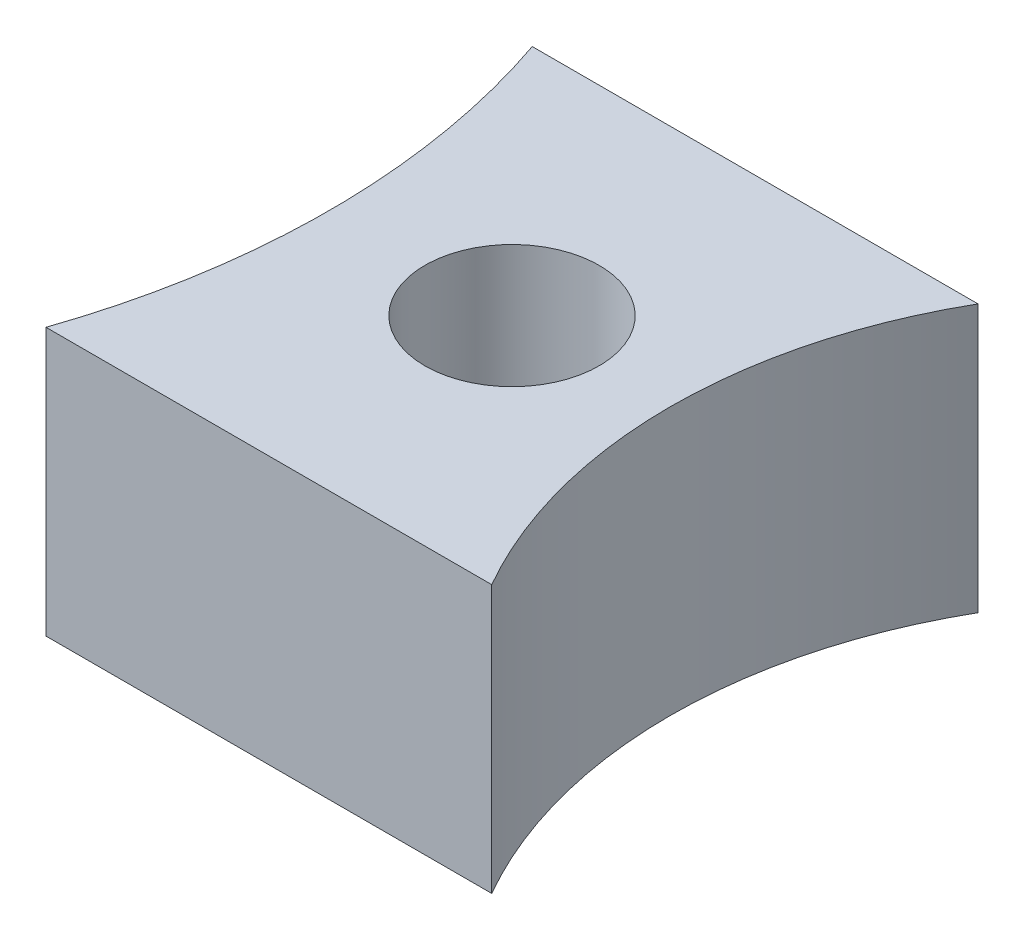
SolidWorks part; units mm, degrees
ref_plane "Front Plane" through (0, 0, 0) normal (0, 0, 1) x (1, 0, 0)
ref_plane "Top Plane" through (0, 0, 0) normal (0, 1, 0) x (1, 0, 0)
ref_plane "Right Plane" through (0, 0, 0) normal (1, 0, 0) x (0, 0, -1)
sketch "Sketch1" plane through (0, 0, 0) normal (0, 1, 0) x (1, 0, 0)
  line L0 (5.5, 0) -> (3.9, 0) construction
  line L1 (-5.5, 6) -> (5.5, 6)
  line L2 (-5.5, 6) -> (-5.5, -6)
  line L3 (-5.5, -6) -> (5.5, -6)
  line L4 (5.5, 6) -> (5.5, -6)
  line L5 (-5.5, 6) -> (5.5, -6) construction
  line L6 (-5.5, -6) -> (5.5, 6) construction
  line L7 (-5.5, 0) -> (-4.5, 0) construction
  circle A0 centre (15.95, 0) radius 12.05
  circle A1 centre (-23, 0) radius 18.5
  point P0 (0, 0)
  dimension "D1" = 12
  dimension "D2" = 11
  dimension "D3" = 1.6
  dimension "D4" = 1
extrude "Boss-Extrude2" add sketch "Sketch1" along normal blind 6.6 contours A1 L3 A0 L1
sketch "Sketch4" plane through (0, 6.6, 0) normal (0, 1, 0) x (1, 0, 0)
  line L0 (0, -6) -> (0, 0) construction
  line L1 (-5.5, -6) -> (5.5, -6) construction
  line L2 (-5.5, -6) -> (0, -6) construction
  circle A0 centre (0, 0) radius 2.15
  point P1 (0, 0)
  point P11 (0, 0)
  dimension "D3" = 4.3
  dimension "D1" = 6
  dimension "D2" = 5.5
hole_wizard "M4 Clearance Hole2" positions "Sketch4" profile "Sketch5" hole size "M4" standard "ANSI Metric" end condition up to next
sketch "Sketch5" plane through (0, 6.6, 0) normal (1, 0, 0) x (0, 0, 1)
  line L0 (0, 0) -> (0, 6.6)
  line L1 (0, 6.6) -> (2.15, 6.6)
  line L2 (2.15, 6.6) -> (2.15, 0)
  line L5 (2.15, 0) -> (0, 0)
  line L11 (0, -6.35) -> (0, 107.95) construction
  dimension "Thru Hole Dia." = 4.3
  dimension "Thru Hole Depth" = 6.6
